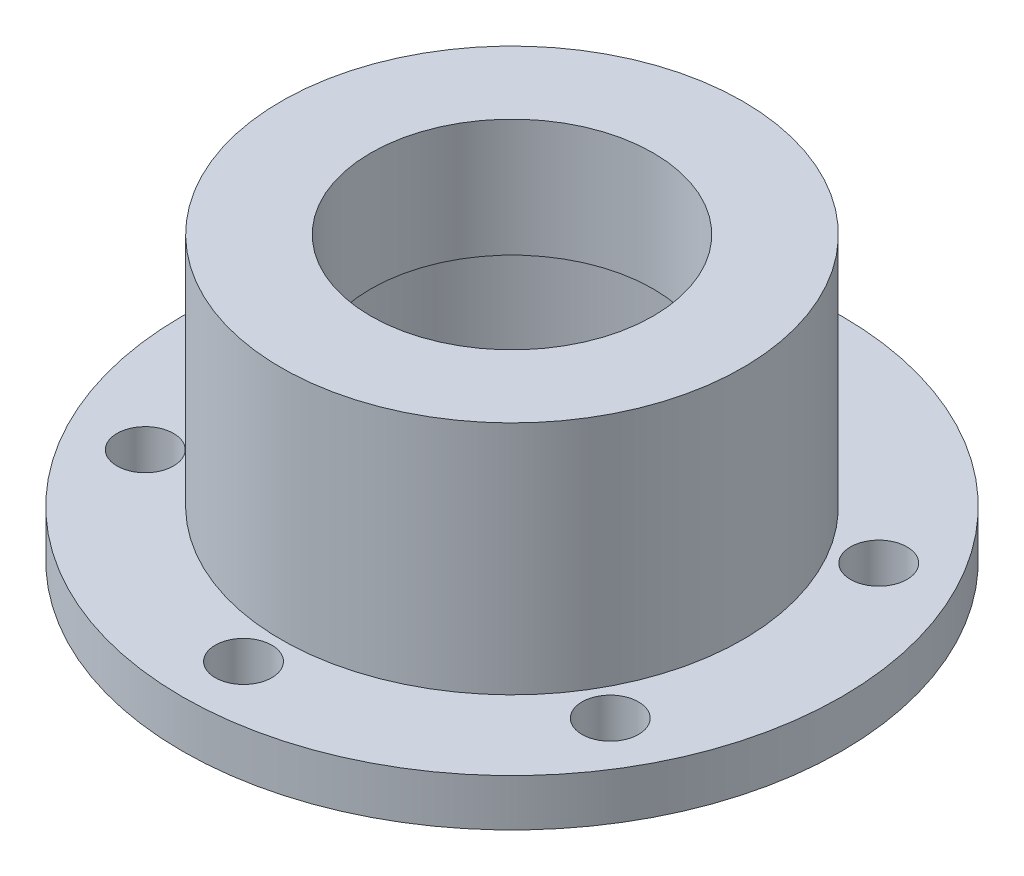
SolidWorks part; units mm, degrees
ref_plane "Front Plane" through (0, 0, 0) normal (0, 0, 1) x (1, 0, 0)
ref_plane "Top Plane" through (0, 0, 0) normal (0, 1, 0) x (1, 0, 0)
ref_plane "Right Plane" through (0, 0, 0) normal (1, 0, 0) x (0, 0, -1)
sketch "Sketch1" plane through (0, 0, 0) normal (0, 0, 1) x (1, 0, 0)
  line L0 (0, 0) -> (0, 100.3231) construction
  line L1 (24.5, 0) -> (35, 0)
  line L2 (35, 0) -> (35, -5)
  line L3 (35, -5) -> (20, -5)
  line L4 (20, -5) -> (20, 12.5)
  line L5 (20, 12.5) -> (15, 12.5)
  line L6 (15, 12.5) -> (15, 25)
  line L7 (15, 25) -> (24.5, 25)
  line L8 (24.5, 0) -> (24.5, 25)
  dimension "D1" = 35
  dimension "D2" = 12.5
  dimension "D3" = 30
  dimension "D4" = 25
  dimension "D5" = 15
  dimension "D6" = 24.5
  dimension "D7" = 20
revolve "Revolve1" add sketch "Sketch1" angle 360 about L0
sketch "Sketch2" plane through (0, 25, 0) normal (0, 1, 0) x (1, 0, 0)
  circle A0 centre (0, 0) radius 28.5 construction
  circle A1 centre (0, 28.5) radius 3
  circle A2 centre (24.6817, 14.25) radius 3
  circle A3 centre (24.6817, -14.25) radius 3
  circle A4 centre (0, -28.5) radius 3
  circle A5 centre (-24.6817, -14.25) radius 3
  circle A6 centre (-24.6817, 14.25) radius 3
  point P17 (0, 0)
  dimension "D1" = 57
  dimension "D2" = 6
  dimension "D3" = 6
extrude "Cut-Extrude3" cut sketch "Sketch2" against normal through all
